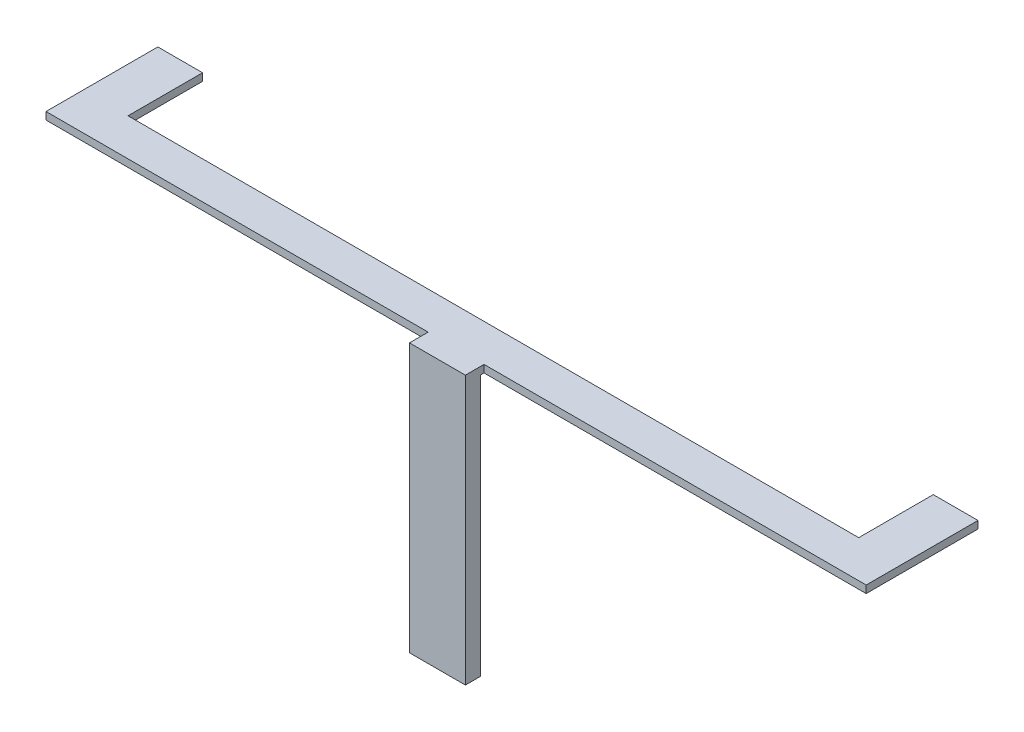
SolidWorks part; units mm, degrees
ref_plane "Front Plane" through (0, 0, 0) normal (0, 0, 1) x (1, 0, 0)
ref_plane "Top Plane" through (0, 0, 0) normal (0, 1, 0) x (1, 0, 0)
ref_plane "Right Plane" through (0, 0, 0) normal (1, 0, 0) x (0, 0, -1)
sketch "Sketch1" plane through (0, 0, 0) normal (0, 1, 0) x (1, 0, 0)
  line L0 (110, 0) -> (110, 12.6347) construction
  line L1 (0, 0) -> (220, 0)
  line L2 (0, 0) -> (0, 10)
  line L3 (0, 10) -> (220, 10)
  line L4 (220, 0) -> (220, 10)
  line L5 (0, 10) -> (12, 10)
  line L6 (0, 10) -> (0, 30)
  line L7 (0, 30) -> (12, 30)
  line L8 (12, 10) -> (12, 30)
  line L9 (220, 10) -> (208, 10)
  line L10 (220, 10) -> (220, 30)
  line L11 (220, 30) -> (208, 30)
  line L12 (208, 10) -> (208, 30)
  line L14 (102.5, 0) -> (117.5, 0)
  line L15 (102.5, 0) -> (102.5, -5)
  line L16 (102.5, -5) -> (117.5, -5)
  line L17 (117.5, 0) -> (117.5, -5)
  point P8 (6, 30)
  point P14 (102.5, 0)
  point P15 (117.5, 0)
  dimension "D1" = 220
  dimension "D2" = 10
  dimension "D3" = 20
  dimension "D4" = 12
  dimension "D5" = 12
  dimension "D6" = 20
  dimension "D7" = 7.5
  dimension "D8" = 7.5
  dimension "D9" = 5
extrude "Boss-Extrude1" add sketch "Sketch1" along normal blind 2 contours L3 L8 L7 L6 | L1 L0 L3 L2 | L17 L14 L1 L15 L16 | L0 L14 L1 L4 L3 | L12 L3 L10 L11
sketch "Sketch2" plane through (0, 0, 0) normal (0, -1, 0) x (1, 0, 0)
  line L0 (117.5, 0) -> (117.5, 5) construction
  line L1 (102.5, 5) -> (117.5, 5)
  line L2 (102.5, 5) -> (102.5, 1)
  line L3 (102.5, 1) -> (117.5, 1)
  line L4 (117.5, 5) -> (117.5, 1)
  dimension "D1" = 4
extrude "Boss-Extrude2" add sketch "Sketch2" along normal blind 70
